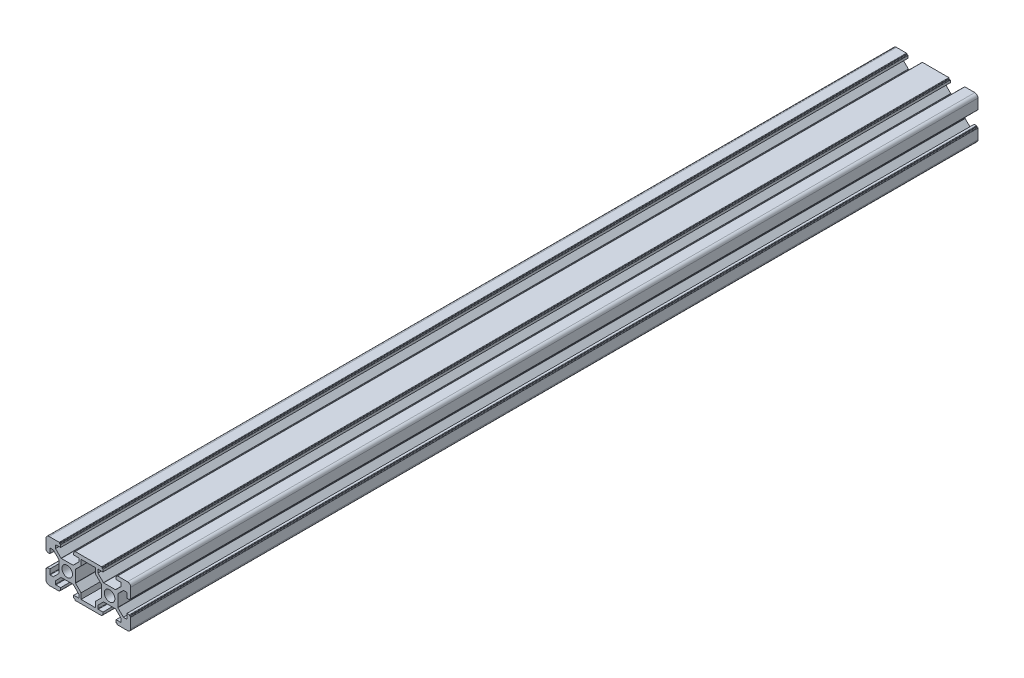
SolidWorks part; units mm, degrees
ref_plane "前视基准面" through (0, 0, 0) normal (0, 0, 1) x (1, 0, 0)
ref_plane "上视基准面" through (0, 0, 0) normal (0, 1, 0) x (1, 0, 0)
ref_plane "右视基准面" through (0, 0, 0) normal (1, 0, 0) x (0, 0, -1)
sketch "Sketch1" plane through (0, 0, 0) normal (0, 0, 1) x (1, 0, 0)
  line L0 (-8.5, 10) -> (-3.8, 10)
  line L3 (-8.5, -10) -> (-3.8, -10)
  line L5 (-10, 8.5) -> (-10, 3.8)
  line L6 (-2.7565, 3.9) -> (2.7565, 3.9)
  line L9 (-2.7565, -3.9) -> (2.7565, -3.9)
  line L10 (3.9, 2.7565) -> (3.9, -2.7565)
  line L11 (-3.9, 2.7565) -> (-3.9, -2.7565)
  line L12 (-3.9586, -2.8979) -> (-6.5607, -5.5)
  line L13 (3.6, 9.7) -> (3.6, 9.8)
  line L14 (3.1, -8.2) -> (5.3, -8.2)
  line L15 (-2.8979, -3.9586) -> (-5.5, -6.5607)
  line L16 (-3.1, -8.2) -> (-3.1, -9.3)
  line L17 (3.1, -8.2) -> (3.1, -9.3)
  line L18 (-5.5, -6.5607) -> (-5.5, -8)
  line L19 (5.5, -6.5607) -> (5.5, -8)
  line L20 (-5.3, -8.2) -> (-3.1, -8.2)
  line L21 (-3.4, -9.5) -> (-3.3, -9.5)
  line L22 (3.8, -10) -> (8.5, -10)
  line L23 (3.3, -9.5) -> (3.4, -9.5)
  line L24 (-3.6, -9.7) -> (-3.6, -9.8)
  line L25 (3.6, -9.7) -> (3.6, -9.8)
  line L26 (-6.5607, -5.5) -> (-8, -5.5)
  line L27 (-9.7, -3.6) -> (-9.8, -3.6)
  line L28 (-9.5, -3.4) -> (-9.5, -3.3)
  line L29 (-8.2, -3.1) -> (-9.3, -3.1)
  line L30 (-8.2, -5.3) -> (-8.2, -3.1)
  line L31 (-10, -3.8) -> (-10, -8.5)
  line L33 (3.8, 10) -> (8.5, 10)
  line L34 (2.8979, -3.9586) -> (5.5, -6.5607)
  line L40 (3.9586, -2.8979) -> (6.5607, -5.5)
  line L41 (3.3, 9.5) -> (3.4, 9.5)
  line L42 (30, 8.5) -> (30, 3.8)
  line L43 (3.1, 8.2) -> (3.1, 9.3)
  line L44 (3.1, 8.2) -> (5.3, 8.2)
  line L45 (5.5, 6.5607) -> (5.5, 8)
  line L46 (2.8979, 3.9586) -> (5.5, 6.5607)
  line L52 (3.9586, 2.8979) -> (6.5607, 5.5)
  line L53 (-3.6, 9.7) -> (-3.6, 9.8)
  line L54 (-3.4, 9.5) -> (-3.3, 9.5)
  line L55 (-3.1, 8.2) -> (-3.1, 9.3)
  line L56 (-5.3, 8.2) -> (-3.1, 8.2)
  line L57 (-5.5, 6.5607) -> (-5.5, 8)
  line L58 (-2.8979, 3.9586) -> (-5.5, 6.5607)
  line L59 (-9.5, 3.4) -> (-9.5, 3.3)
  line L60 (-9.7, 3.6) -> (-9.8, 3.6)
  line L61 (-8.2, 3.1) -> (-9.3, 3.1)
  line L62 (-8.2, 5.3) -> (-8.2, 3.1)
  line L63 (-6.5607, 5.5) -> (-8, 5.5)
  line L64 (-3.9586, 2.8979) -> (-6.5607, 5.5)
  line L65 (29.7, 3.6) -> (29.8, 3.6)
  line L66 (29.5, 3.4) -> (29.5, 3.3)
  line L67 (28.2, 3.1) -> (29.3, 3.1)
  line L68 (28.2, 5.3) -> (28.2, 3.1)
  line L69 (26.5607, 5.5) -> (28, 5.5)
  line L70 (23.9586, 2.8979) -> (26.5607, 5.5)
  line L71 (23.9, 2.7565) -> (23.9, -2.7565)
  line L72 (23.9586, -2.8979) -> (26.5607, -5.5)
  line L73 (26.5607, -5.5) -> (28, -5.5)
  line L74 (28.2, -5.3) -> (28.2, -3.1)
  line L75 (28.2, -3.1) -> (29.3, -3.1)
  line L76 (29.5, -3.4) -> (29.5, -3.3)
  line L77 (29.7, -3.6) -> (29.8, -3.6)
  line L78 (30, -3.8) -> (30, -8.5)
  line L79 (28.5, -10) -> (23.8, -10)
  line L80 (23.6, -9.7) -> (23.6, -9.8)
  line L81 (23.4, -9.5) -> (23.3, -9.5)
  line L82 (23.1, -8.2) -> (23.1, -9.3)
  line L83 (25.3, -8.2) -> (23.1, -8.2)
  line L84 (25.5, -6.5607) -> (25.5, -8)
  line L85 (22.8979, -3.9586) -> (25.5, -6.5607)
  line L86 (22.7565, -3.9) -> (17.2435, -3.9)
  line L87 (17.1021, -3.9586) -> (14.5, -6.5607)
  line L88 (14.5, -6.5607) -> (14.5, -8)
  line L89 (16.9, -8.2) -> (14.7, -8.2)
  line L90 (16.9, -8.2) -> (16.9, -9.3)
  line L91 (16.7, -9.5) -> (16.6, -9.5)
  line L92 (16.4, -9.7) -> (16.4, -9.8)
  line L93 (16.2, -10) -> (11.5, -10)
  line L94 (13.4393, 5.5) -> (13.4393, 8.2)
  line L96 (6.5607, 5.5) -> (6.5607, 8.2)
  line L97 (6.5607, 8.2) -> (13.4393, 8.2)
  line L99 (16.0414, -2.8979) -> (13.4393, -5.5)
  line L100 (16.1, 2.7565) -> (16.1, -2.7565)
  line L101 (16.0414, 2.8979) -> (13.4393, 5.5)
  line L107 (16.2, 10) -> (11.5, 10)
  line L108 (16.4, 9.7) -> (16.4, 9.8)
  line L109 (16.7, 9.5) -> (16.6, 9.5)
  line L110 (16.9, 8.2) -> (16.9, 9.3)
  line L111 (16.9, 8.2) -> (14.7, 8.2)
  line L112 (14.5, 6.5607) -> (14.5, 8)
  line L113 (17.1021, 3.9586) -> (14.5, 6.5607)
  line L114 (22.7565, 3.9) -> (17.2435, 3.9)
  line L115 (22.8979, 3.9586) -> (25.5, 6.5607)
  line L116 (25.5, 6.5607) -> (25.5, 8)
  line L117 (25.3, 8.2) -> (23.1, 8.2)
  line L118 (23.1, 8.2) -> (23.1, 9.3)
  line L119 (23.4, 9.5) -> (23.3, 9.5)
  line L120 (23.6, 9.7) -> (23.6, 9.8)
  line L121 (28.5, 10) -> (23.8, 10)
  line L122 (13.4393, -5.5) -> (13.4393, -8.2)
  line L124 (6.5607, -5.5) -> (6.5607, -8.2)
  line L125 (6.5607, -8.2) -> (13.4393, -8.2)
  line L127 (8.5, 10) -> (11.5, 10)
  line L128 (8.5, -10) -> (11.5, -10)
  arc A3 (-8.5, -10) -> (-10, -8.5) centre (-8.5, -8.5) cw
  arc A4 (-10, 8.5) -> (-8.5, 10) centre (-8.5, 8.5) cw
  arc A5 (3.4, -9.5) -> (3.6, -9.7) centre (3.4, -9.7) cw
  arc A6 (3.8, -10) -> (3.6, -9.8) centre (3.8, -9.8) cw
  arc A7 (3.3, -9.5) -> (3.1, -9.3) centre (3.3, -9.3) cw
  arc A8 (5.3, -8.2) -> (5.5, -8) centre (5.3, -8) ccw
  arc A9 (-3.9, -2.7565) -> (-3.9586, -2.8979) centre (-4.1, -2.7565) cw
  arc A10 (-3.9, 2.7565) -> (-3.9586, 2.8979) centre (-4.1, 2.7565) ccw
  arc A11 (-2.7565, 3.9) -> (-2.8979, 3.9586) centre (-2.7565, 4.1) cw
  arc A12 (2.7565, 3.9) -> (2.8979, 3.9586) centre (2.7565, 4.1) ccw
  arc A13 (3.9586, 2.8979) -> (3.9, 2.7565) centre (4.1, 2.7565) ccw
  arc A14 (3.9, -2.7565) -> (3.9586, -2.8979) centre (4.1, -2.7565) ccw
  arc A15 (-2.8979, -3.9586) -> (-2.7565, -3.9) centre (-2.7565, -4.1) cw
  arc A16 (2.7565, -3.9) -> (2.8979, -3.9586) centre (2.7565, -4.1) cw
  arc A17 (-3.6, -9.8) -> (-3.8, -10) centre (-3.8, -9.8) cw
  arc A18 (-3.3, -9.5) -> (-3.1, -9.3) centre (-3.3, -9.3) ccw
  arc A19 (-3.6, -9.7) -> (-3.4, -9.5) centre (-3.4, -9.7) cw
  arc A20 (-8.2, 5.3) -> (-8, 5.5) centre (-8, 5.3) cw
  arc A23 (-8.2, -5.3) -> (-8, -5.5) centre (-8, -5.3) ccw
  arc A24 (-5.3, -8.2) -> (-5.5, -8) centre (-5.3, -8) cw
  arc A31 (3.1, 9.3) -> (3.3, 9.5) centre (3.3, 9.3) cw
  arc A32 (3.6, 9.8) -> (3.8, 10) centre (3.8, 9.8) cw
  arc A33 (3.6, 9.7) -> (3.4, 9.5) centre (3.4, 9.7) cw
  arc A34 (-3.8, 10) -> (-3.6, 9.8) centre (-3.8, 9.8) cw
  arc A35 (-3.3, 9.5) -> (-3.1, 9.3) centre (-3.3, 9.3) cw
  arc A36 (-3.4, 9.5) -> (-3.6, 9.7) centre (-3.4, 9.7) cw
  arc A37 (5.5, 8) -> (5.3, 8.2) centre (5.3, 8) ccw
  arc A38 (-5.5, 8) -> (-5.3, 8.2) centre (-5.3, 8) cw
  arc A39 (-10, 3.8) -> (-9.8, 3.6) centre (-9.8, 3.8) ccw
  arc A40 (-9.5, 3.3) -> (-9.3, 3.1) centre (-9.3, 3.3) ccw
  arc A41 (-9.7, 3.6) -> (-9.5, 3.4) centre (-9.7, 3.4) cw
  arc A42 (-10, -3.8) -> (-9.8, -3.6) centre (-9.8, -3.8) cw
  arc A43 (-9.5, -3.3) -> (-9.3, -3.1) centre (-9.3, -3.3) cw
  arc A44 (-9.5, -3.4) -> (-9.7, -3.6) centre (-9.7, -3.4) cw
  arc A45 (30, 8.5) -> (28.5, 10) centre (28.5, 8.5) ccw
  arc A46 (30, 3.8) -> (29.8, 3.6) centre (29.8, 3.8) cw
  arc A47 (29.7, 3.6) -> (29.5, 3.4) centre (29.7, 3.4) ccw
  arc A48 (29.5, 3.3) -> (29.3, 3.1) centre (29.3, 3.3) cw
  arc A49 (28.2, 5.3) -> (28, 5.5) centre (28, 5.3) ccw
  arc A50 (23.9, 2.7565) -> (23.9586, 2.8979) centre (24.1, 2.7565) cw
  arc A51 (23.9, -2.7565) -> (23.9586, -2.8979) centre (24.1, -2.7565) ccw
  arc A52 (28.2, -5.3) -> (28, -5.5) centre (28, -5.3) cw
  arc A53 (29.5, -3.3) -> (29.3, -3.1) centre (29.3, -3.3) ccw
  arc A54 (29.5, -3.4) -> (29.7, -3.6) centre (29.7, -3.4) ccw
  arc A55 (30, -3.8) -> (29.8, -3.6) centre (29.8, -3.8) ccw
  arc A56 (28.5, -10) -> (30, -8.5) centre (28.5, -8.5) ccw
  arc A57 (23.6, -9.8) -> (23.8, -10) centre (23.8, -9.8) ccw
  arc A58 (23.6, -9.7) -> (23.4, -9.5) centre (23.4, -9.7) ccw
  arc A59 (23.3, -9.5) -> (23.1, -9.3) centre (23.3, -9.3) cw
  arc A60 (25.3, -8.2) -> (25.5, -8) centre (25.3, -8) ccw
  arc A61 (22.8979, -3.9586) -> (22.7565, -3.9) centre (22.7565, -4.1) ccw
  arc A62 (17.2435, -3.9) -> (17.1021, -3.9586) centre (17.2435, -4.1) ccw
  arc A63 (14.7, -8.2) -> (14.5, -8) centre (14.7, -8) cw
  arc A64 (16.7, -9.5) -> (16.9, -9.3) centre (16.7, -9.3) ccw
  arc A65 (16.6, -9.5) -> (16.4, -9.7) centre (16.6, -9.7) ccw
  arc A66 (16.2, -10) -> (16.4, -9.8) centre (16.2, -9.8) ccw
  arc A72 (16.1, -2.7565) -> (16.0414, -2.8979) centre (15.9, -2.7565) cw
  arc A73 (16.0414, 2.8979) -> (16.1, 2.7565) centre (15.9, 2.7565) cw
  arc A79 (16.4, 9.8) -> (16.2, 10) centre (16.2, 9.8) ccw
  arc A80 (16.4, 9.7) -> (16.6, 9.5) centre (16.6, 9.7) ccw
  arc A81 (16.9, 9.3) -> (16.7, 9.5) centre (16.7, 9.3) ccw
  arc A82 (14.5, 8) -> (14.7, 8.2) centre (14.7, 8) cw
  arc A83 (17.2435, 3.9) -> (17.1021, 3.9586) centre (17.2435, 4.1) cw
  arc A84 (22.7565, 3.9) -> (22.8979, 3.9586) centre (22.7565, 4.1) ccw
  arc A85 (25.5, 8) -> (25.3, 8.2) centre (25.3, 8) ccw
  arc A86 (23.3, 9.5) -> (23.1, 9.3) centre (23.3, 9.3) ccw
  arc A87 (23.4, 9.5) -> (23.6, 9.7) centre (23.4, 9.7) ccw
  arc A88 (23.8, 10) -> (23.6, 9.8) centre (23.8, 9.8) ccw
  point P11 (3.9, 3.9)
  point P19 (3.3697, 4.4303)
  point P20 (-10.6428, -10.6428)
  point P25 (-11.1731, -10.1124)
  point P26 (4.4303, 3.3697)
  point P28 (-10.1124, -11.1731)
  dimension "D3" = 0.2
  dimension "D4" = 0.2
  dimension "D5" = 0.2
  dimension "D8" = 0.2
  dimension "D9" = 0.2
  dimension "D10" = 0.2
  dimension "D6" = 1.8
  dimension "D7" = 0.5
extrude "Boss-Extrude1" add sketch "Sketch1" along normal blind 400
ref_plane "hole" through (0, 0, 400) normal (0, 0, 1) x (1, 0, 0)
sketch "Sketch2" plane through (0, 0, 400) normal (0, 0, 1) x (1, 0, 0)
  circle A0 centre (0, 0) radius 2.5
  circle A1 centre (20, 0) radius 2.5
  dimension "D1" = 5
extrude "Cut-Extrude1" cut sketch "Sketch2" against normal through all
